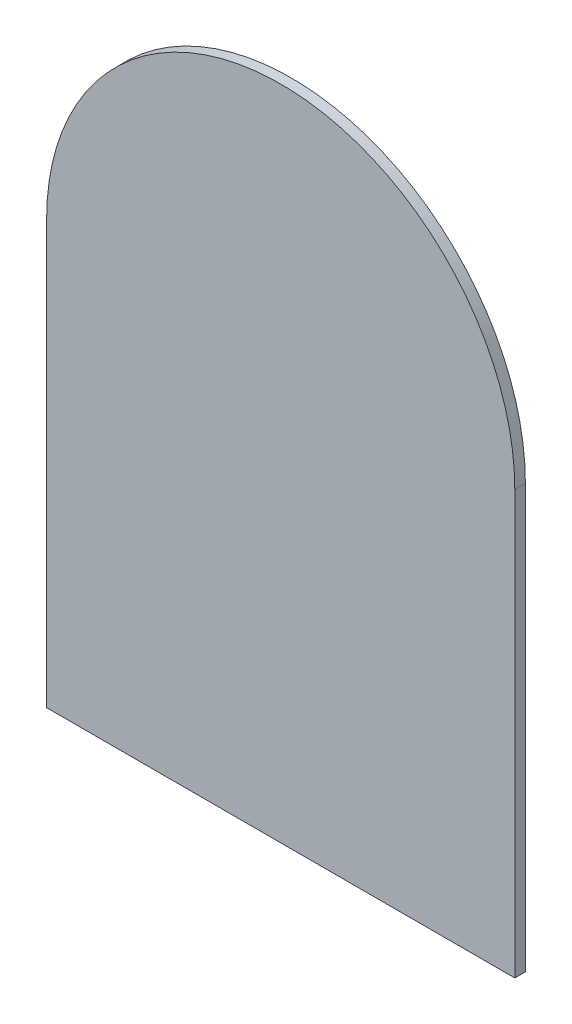
SolidWorks part; units mm, degrees
material "Glass"
ref_plane "Front Plane" through (0, 0, 0) normal (0, 0, 1) x (1, 0, 0)
ref_plane "Top Plane" through (0, 0, 0) normal (0, 1, 0) x (1, 0, 0)
ref_plane "Right Plane" through (0, 0, 0) normal (1, 0, 0) x (0, 0, -1)
sketch "Sketch1" plane through (0, 0, 0) normal (0, 0, 1) x (1, 0, 0)
  line L1 (0, 0) -> (-442.62, 0)
  line L2 (0, 0) -> (0, 400)
  line L4 (-442.62, 0) -> (-442.62, 400)
  arc A0 (0, 400) -> (-442.62, 400) centre (-221.31, 400) ccw
  dimension "D1" = 442.62
  dimension "D2" = 400
extrude "Boss-Extrude1" add sketch "Sketch1" along normal blind 10
